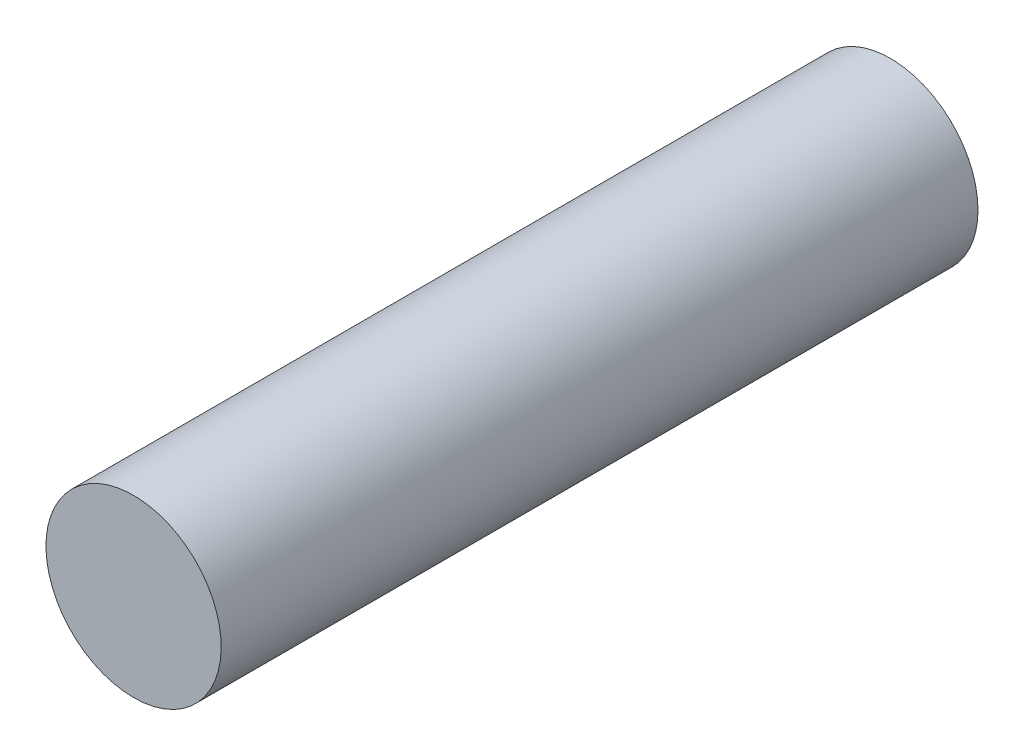
SolidWorks part; units mm, degrees
ref_plane "前视基准面" through (0, 0, 0) normal (0, 0, 1) x (1, 0, 0)
ref_plane "上视基准面" through (0, 0, 0) normal (0, 1, 0) x (1, 0, 0)
ref_plane "右视基准面" through (0, 0, 0) normal (1, 0, 0) x (0, 0, -1)
other "Configuration Table"
sketch "草图2" plane through (0, 0, 0) normal (0, 0, 1) x (1, 0, 0)
  line L8 (-44.55, -13.5) -> (-3.1668, -13.5)
  line L9 (5.45, -15) -> (5.45, -32.5)
  line L10 (5.45, -32.5) -> (100, -32.5)
  line L11 (100, -32.5) -> (100, 34.5)
  line L12 (100, 34.5) -> (-100, 34.5)
  line L13 (-100, 34.5) -> (-100, 5)
  line L14 (-100, 5) -> (-44.55, 5)
  line L15 (-44.55, 5) -> (-44.55, -13.5)
  line L16 (-44.55, -13.5) -> (-3.1668, -13.5)
  line L17 (5.45, -15) -> (5.45, -32.5)
  line L18 (5.45, -32.5) -> (100, -32.5)
  line L19 (100, -32.5) -> (100, 34.5)
  line L20 (100, 34.5) -> (-100, 34.5)
  line L21 (-100, 34.5) -> (-100, 5)
  line L22 (-100, 5) -> (-44.55, 5)
  line L23 (-44.55, 5) -> (-44.55, -13.5)
  circle A0 centre (5.45, 10.5) radius 5.05 construction
  arc A1 (-3.1668, -13.5) -> (5.45, -15) centre (5.45, 10.5) ccw
  arc A2 (-3.1668, -13.5) -> (5.45, -15) centre (5.45, 10.5) ccw
  circle A3 centre (5.45, 10.5) radius 5.05
  circle A4 centre (5.45, 10.5) radius 5
  line M20 (10.2, 15.15) -> (-2.8, 15.15)
  dimension "D2" = 10
  dimension "D1" = 0
extrude "凸台-拉伸1" add sketch "草图2" along normal blind 40 contours A4 M20 | A4 M20
sketch "草图3" plane through (0, 0, 40) normal (0, 0, 1) x (1, 0, 0)
  circle A1 centre (5.45, 10.5) radius 5
  circle A2 centre (5.45, 10.5) radius 5
  dimension "D1" = 0
extrude "凸台-拉伸2" add sketch "草图3" along normal up to surface (3.2 mm away)
